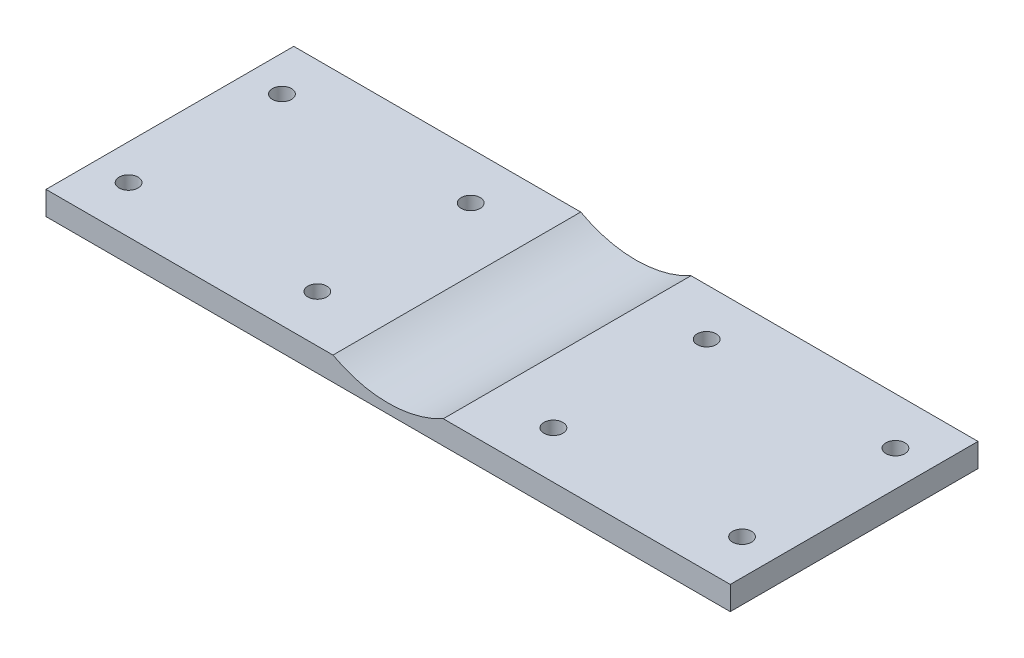
SolidWorks part; units mm, degrees
ref_plane "Front Plane" through (0, 0, 0) normal (0, 0, 1) x (1, 0, 0)
ref_plane "Top Plane" through (0, 0, 0) normal (0, 1, 0) x (1, 0, 0)
ref_plane "Right Plane" through (0, 0, 0) normal (1, 0, 0) x (0, 0, -1)
sketch "Sketch1" plane through (0, 0, 0) normal (0, 1, 0) x (1, 0, 0)
  line L1 (0, 0) -> (184.15, 0)
  line L2 (0, 0) -> (0, 66.675)
  line L3 (0, 66.675) -> (184.15, 66.675)
  line L4 (184.15, 0) -> (184.15, 66.675)
  dimension "D1" = 184.15
  dimension "D2" = 66.675
extrude "Boss-Extrude1" add sketch "Sketch1" along normal blind 10.541
sketch "Sketch4" plane through (0, 0, 0) normal (0, 0, 1) x (1, 0, 0)
  line L0 (0, 0) -> (184.15, 0) construction
  line L1 (53.975, 0) -> (130.175, 0)
  line L2 (53.975, 0) -> (53.975, -6.35)
  line L3 (53.975, -6.35) -> (130.175, -6.35)
  line L4 (130.175, 0) -> (130.175, -6.35)
  line L5 (92.075, 10.541) -> (92.075, -52.0257) construction
  line L6 (0, 10.541) -> (184.15, 10.541) construction
  dimension "D1" = 76.2
  dimension "D2" = 6.35
extrude "Boss-Extrude2" add sketch "Sketch4" against normal up to surface (66.675 mm away) up to face at (92.075, 5.2705, -66.675)
sketch "Sketch5" plane through (0, 10.541, 0) normal (0, 1, 0) x (1, 0, 0)
  line L0 (184.15, 66.675) -> (0, 66.675) construction
  line L1 (119.0625, 66.675) -> (65.0875, 66.675)
  line L2 (119.0625, 66.675) -> (119.0625, 0)
  line L3 (119.0625, 0) -> (65.0875, 0)
  line L4 (65.0875, 66.675) -> (65.0875, 0)
  line L5 (0, 0) -> (184.15, 0) construction
  line L6 (92.075, 66.675) -> (92.075, -25.2417) construction
  dimension "D1" = 53.975
extrude "Cut-Extrude1" cut sketch "Sketch5" against normal blind 9.525
sketch "Sketch17" plane through (0, 0, 0) normal (0, 0, 1) x (1, 0, 0)
  line L1 (130.175, -6.35) -> (184.15, -6.35)
  line L2 (130.175, -6.35) -> (130.175, 0)
  line L3 (130.175, 0) -> (184.15, 0)
  line L4 (184.15, -6.35) -> (184.15, 0)
extrude "Boss-Extrude3" add sketch "Sketch17" against normal up to vertex (66.675 mm away) up to point (184.15, 0, -66.675)
hole_wizard "#10 Clearance Hole1" positions "Sketch2" profile "Sketch3" hole size "#10" standard "ANSI Inch" end condition through all
sketch "Sketch2" plane through (0, 10.541, 0) normal (0, 1, 0) x (1, 0, 0)
  line L0 (0, 66.675) -> (0, 0) construction
  line L1 (184.15, 66.675) -> (119.0625, 66.675) construction
  line L2 (0, 0) -> (65.0875, 0) construction
  line L3 (184.15, 0) -> (184.15, 66.675) construction
  line L4 (53.975, 66.675) -> (0, 66.675) construction
  line L7 (184.15, 66.675) -> (53.975, 66.675) construction
  point P0 (9.525, 53.975)
  point P2 (9.525, 12.7)
  point P4 (60.325, 12.7)
  point P6 (60.325, 53.975)
  point P8 (123.825, 53.975)
  point P10 (123.8498, 12.7)
  point P12 (174.625, 12.7)
  point P14 (174.625, 53.975)
  dimension "D1" = 9.525
  dimension "D2" = 12.7
  dimension "D3" = 9.525
  dimension "D4" = 12.7
  dimension "D5" = 12.7
  dimension "D6" = 50.8
  dimension "D7" = 12.7
  dimension "D8" = 50.8
  dimension "D9" = 41.275
  dimension "D10" = 9.525
  dimension "D11" = 12.7
  dimension "D12" = 9.525
  dimension "D13" = 50.8
  dimension "D14" = 41.275
  dimension "D15" = 12.7
sketch "Sketch3" plane through (9.525, 10.541, -53.975) normal (1, 0, 0) x (0, 0, 1)
  line L0 (0, 0) -> (0, 16.891)
  line L1 (0, 16.891) -> (2.5527, 16.891)
  line L2 (2.5527, 16.891) -> (2.5527, 0)
  line L5 (2.5527, 0) -> (0, 0)
  line L11 (0, -6.35) -> (0, 107.95) construction
  dimension "Thru Hole Dia." = 5.1054
  dimension "Thru Hole Depth" = 16.891
ref_plane "Plane1" through (92.075, 0, 0) normal (-1, 0, 0) x (0, 0, 1)
sketch "Sketch12" plane through (0, 0, -66.675) normal (0, 0, -1) x (-1, 0, 0)
  circle A0 centre (-92.075, 27.2394) radius 31.0193
extrude "Cut-Extrude3" cut sketch "Sketch12" against normal through all contours A0
sketch "Sketch14" [suppressed] plane through (0, 0, 0) normal (0, 0, 1) x (1, 0, 0)
  line L2 (113.9825, 0) -> (184.15, 0) construction
  line L3 (119.0625, 5.08) -> (119.0625, 9.525) construction
  line L5 (113.9825, 0) -> (119.0625, 0)
  line L6 (119.0625, 5.08) -> (119.0625, 0)
  arc A0 (113.9825, 0) -> (119.0625, 5.08) centre (113.9825, 5.08) ccw construction
  arc A2 (113.9825, 0) -> (119.0625, 5.08) centre (113.9825, 5.08) ccw
extrude "Cut-Extrude5" [suppressed] cut sketch "Sketch14" against normal through all
sketch "Sketch15" [suppressed] plane through (0, 0, 0) normal (0, 0, 1) x (1, 0, 0)
  line L0 (0, 0) -> (70.1675, 0) construction
  line L1 (65.0875, 5.08) -> (65.0875, 9.525) construction
  line L2 (65.0875, 0) -> (70.1675, 0)
  line L3 (65.0875, 5.08) -> (65.0875, 0)
  arc A0 (65.0875, 5.08) -> (70.1675, 0) centre (70.1675, 5.08) ccw construction
  arc A1 (65.0875, 5.08) -> (70.1675, 0) centre (70.1675, 5.08) ccw
extrude "Cut-Extrude6" [suppressed] cut sketch "Sketch15" against normal through all
sketch "Sketch16" [suppressed] plane through (0, 0, 0) normal (0, 0, 1) x (1, 0, 0)
  line L1 (0, 9.525) -> (184.15, 9.525)
  line L2 (0, 9.525) -> (0, 0)
  line L3 (0, 0) -> (184.15, 0)
  line L4 (184.15, 9.525) -> (184.15, 0)
extrude "Cut-Extrude7" [suppressed] cut sketch "Sketch16" against normal through all
sketch "Sketch18" plane through (0, 0, 0) normal (0, 0, 1) x (1, 0, 0)
  line L1 (53.975, -6.35) -> (0, -6.35)
  line L2 (53.975, -6.35) -> (53.975, 0)
  line L3 (53.975, 0) -> (0, 0)
  line L4 (0, -6.35) -> (0, 0)
extrude "Boss-Extrude4" add sketch "Sketch18" against normal up to vertex (66.675 mm away) up to point (0, 0, -66.675)
sketch "Sketch20" plane through (0, 0, 0) normal (0, 0, 1) x (1, 0, 0)
  line L0 (119.0625, 1.016) -> (119.0625, 10.541) construction
  line L1 (65.0875, 1.016) -> (119.0625, 1.016)
  line L2 (65.0875, 1.016) -> (65.0875, 0)
  line L3 (65.0875, 0) -> (119.0625, 0)
  line L4 (119.0625, 1.016) -> (119.0625, 0)
  dimension "D1" = 0
  dimension "D2" = 1.016
extrude "Cut-Extrude8" cut sketch "Sketch20" against normal through all
sketch "Sketch21" plane through (0, 0, 0) normal (0, 1, 0) x (1, 0, 0)
  circle A0 centre (9.525, 12.7) radius 2.5527
  circle A1 centre (9.525, 53.975) radius 2.5527
extrude "Cut-Extrude9" cut sketch "Sketch21" against normal through all
sketch "Sketch22" plane through (0, 0, 0) normal (0, 0, 1) x (1, 0, 0)
  line L0 (184.15, 10.541) -> (184.15, -6.35) construction
  line L1 (0, 10.541) -> (184.15, 10.541)
  line L2 (0, 10.541) -> (0, 0)
  line L3 (0, 0) -> (184.15, 0)
  line L4 (184.15, 10.541) -> (184.15, 0)
  dimension "D1" = 10.541
extrude "Cut-Extrude10" cut sketch "Sketch22" against normal through all
